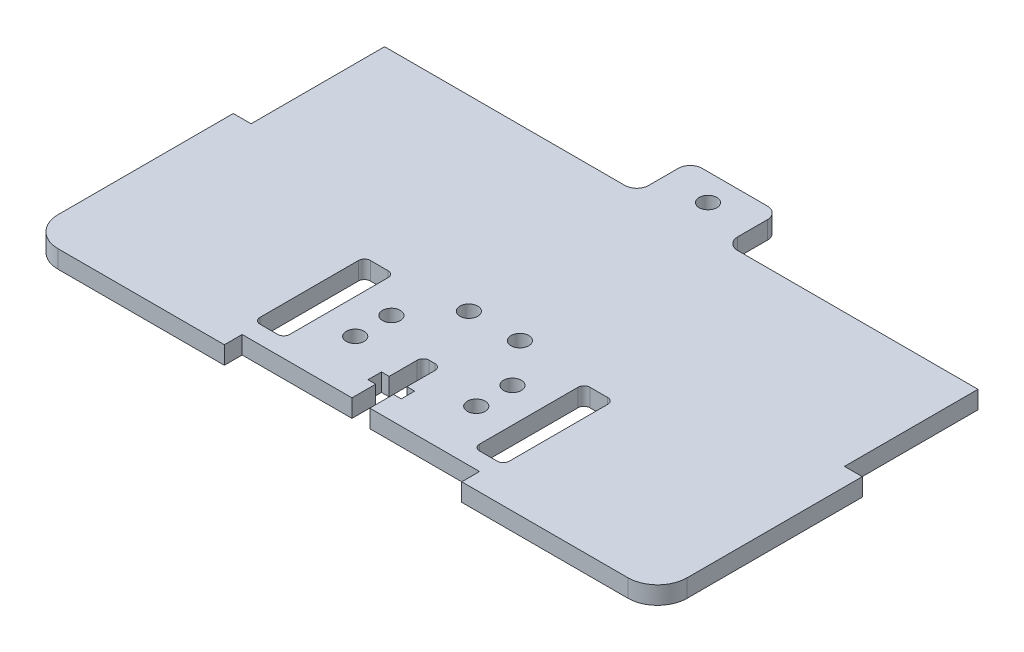
SolidWorks part; units mm, degrees
material "Acrylic (Medium-high impact)"
ref_plane "Plano frontal" through (0, 0, 0) normal (0, 0, 1) x (1, 0, 0)
ref_plane "Plano superior" through (0, 0, 0) normal (0, 1, 0) x (1, 0, 0)
ref_plane "Plano direito" through (0, 0, 0) normal (1, 0, 0) x (0, 0, -1)
sketch "Sketch1" plane through (0, 0, 0) normal (0, 1, 0) x (1, 0, 0)
  line L1 (-53, 28.5) -> (53, 28.5)
  line L2 (-53, 28.5) -> (-53, -28.5)
  line L3 (-53, -28.5) -> (53, -28.5)
  line L4 (53, 28.5) -> (53, -28.5)
  point P4 (0, 28.5)
  point P6 (-53, 0)
  dimension "D1" = 57
  dimension "D2" = 106
extrude "Boss-Extrude1" add sketch "Sketch1" along normal mid plane 3
sketch "Sketch2" plane through (0, 0, 0) normal (0, 1, 0) x (1, 0, 0)
  line L0 (0, -1.65) -> (0, 1.65) construction
  line L1 (-53, 28.5) -> (-50, 28.5)
  line L2 (-53, 28.5) -> (-53, 6)
  line L3 (-53, 6) -> (-50, 6)
  line L4 (-50, 28.5) -> (-50, 6)
  line L5 (50, 28.5) -> (50, 6)
  line L6 (53, 6) -> (50, 6)
  line L7 (53, 28.5) -> (53, 6)
  line L8 (53, 28.5) -> (50, 28.5)
  line L9 (-53, -28.5) -> (53, -28.5) construction
  line L10 (-20, -28.5) -> (20, -28.5)
  line L11 (-20, -28.5) -> (-20, -25.5)
  line L12 (-20, -25.5) -> (20, -25.5)
  line L13 (20, -28.5) -> (20, -25.5)
  point P17 (0, -25.5)
  dimension "D1" = 3
  dimension "D2" = 22.5
  dimension "D3" = 3
  dimension "D4" = 40
extrude "Cut-Extrude1" cut sketch "Sketch2" against normal through all both and the other way through all
sketch "Sketch4" plane through (0, 0, 0) normal (0, 1, 0) x (1, 0, 0)
  line L0 (50, 28.5) -> (-50, 28.5) construction
  line L1 (-7.5, 28.5) -> (7.5, 28.5)
  line L2 (-7.5, 28.5) -> (-7.5, 37.5)
  line L3 (-7.5, 37.5) -> (7.5, 37.5)
  line L4 (7.5, 28.5) -> (7.5, 37.5)
  point P6 (0, 28.5)
  dimension "D1" = 15
  dimension "D2" = 9
extrude "Boss-Extrude2" add sketch "Sketch4" along normal mid plane 3
fillet "Fillet1" radius 2 4 edges at (7.5, 0, -37.5) (-7.5, 0, -37.5) (7.5, 0, -28.5) (-7.5, 0, -28.5)
sketch "Sketch3" plane through (0, 0, 0) normal (0, 1, 0) x (1, 0, 0)
  line L0 (20, -25.5) -> (-20, -25.5) construction
  line L1 (-1.5, -25.5) -> (1.5, -25.5)
  line L2 (-1.5, -25.5) -> (-1.5, -21.5)
  line L3 (-0.5, -13.5) -> (0.5, -13.5)
  line L4 (1.5, -25.5) -> (1.5, -21.5)
  line L5 (1.5, -19.23) -> (2.8, -19.23)
  line L6 (-2.8, -19.23) -> (-1.5, -19.23)
  line L7 (-2.8, -19.23) -> (-2.8, -21.5)
  line L8 (-2.8, -21.5) -> (-1.5, -21.5)
  line L9 (2.8, -19.23) -> (2.8, -21.5)
  line L10 (-1.5, -19.23) -> (-1.5, -14.5)
  line L11 (1.5, -21.5) -> (2.8, -21.5)
  line L12 (1.5, -19.23) -> (1.5, -14.5)
  arc A0 (0.5, -13.5) -> (1.5, -14.5) centre (0.5, -14.5) cw
  arc A1 (-1.5, -14.5) -> (-0.5, -13.5) centre (-0.5, -14.5) cw
  point P6 (0, -13.5)
  dimension "D7" = 1
  dimension "D1" = 3
  dimension "D2" = 2.27
  dimension "D3" = 1.3
  dimension "D4" = 1.3
  dimension "D5" = 4
  dimension "D6" = 12
extrude "Cut-Extrude2" cut sketch "Sketch3" against normal through all both and the other way through all
sketch "Sketch5" plane through (0, 0, 0) normal (0, 1, 0) x (1, 0, 0)
  line L0 (-9.5, 28.5) -> (-50, 28.5) construction
  circle A0 centre (0, 33) radius 1.5
  dimension "D1" = 3
  dimension "D2" = 4.5
extrude "Cut-Extrude3" cut sketch "Sketch5" against normal through all both and the other way through all
fillet "Fillet2" radius 5 2 edges at (53, 0, 28.5) (-53, 0, 28.5)
sketch "Sketch6" plane through (0, 0, 0) normal (0, 1, 0) x (1, 0, 0)
  line L0 (0.5, -13.5) -> (-0.5, -13.5) construction
  line L3 (0, -1.65) -> (0, 1.65) construction
  line L4 (-50, 6) -> (-50, -28.0826) construction
  line L7 (-4.3, -3) -> (4.3, -3) construction
  circle A0 centre (-4.3, -3) radius 1.5
  circle A1 centre (4.3, -3) radius 1.5
  arc A4 (-53, -23.5) -> (-48, -28.5) centre (-48, -23.5) ccw construction
  circle A5 centre (10.2, -10.15) radius 1.5
  circle A11 centre (10.2, -16.25) radius 1.5
  circle A12 centre (-10.2, -16.25) radius 1.5
  circle A13 centre (-10.2, -10.15) radius 1.5
  point P4 (0, -3)
  dimension "D1" = 3
  dimension "D2" = 8.6
  dimension "D3" = 10.5
  dimension "D4" = 3
extrude "Cut-Extrude4" cut sketch "Sketch6" against normal through all both and the other way through all
sketch "Esboço1" plane through (0, 1.5, 0) normal (0, 1, 0) x (1, 0, 0)
  line L0 (-1.5, -25.5) -> (-20, -25.5) construction
  line L1 (-22, -2.9) -> (-15, -2.9) construction
  line L2 (-22, -2.9) -> (-22, -23.5) construction
  line L3 (-22, -23.5) -> (-15, -23.5) construction
  line L4 (-15, -2.9) -> (-15, -23.5) construction
  line L5 (-20, -3.9) -> (-17, -3.9)
  line L6 (-16, -4.9) -> (-16, -21.5)
  line L7 (-20, -22.5) -> (-17, -22.5)
  line L8 (-21, -4.9) -> (-21, -21.5)
  line L18 (-16, -3.9) -> (-16, -22.5) construction
  line L19 (-21, -22.5) -> (-16, -22.5) construction
  line L20 (-21, -3.9) -> (-21, -22.5) construction
  line L21 (-21, -3.9) -> (-16, -3.9) construction
  line L22 (0, -1.65) -> (0, 1.65) construction
  line L23 (15, -2.9) -> (15, -23.5) construction
  line L24 (22, -23.5) -> (15, -23.5) construction
  line L25 (22, -2.9) -> (22, -23.5) construction
  line L26 (22, -2.9) -> (15, -2.9) construction
  line L27 (21, -4.9) -> (21, -21.5)
  line L28 (20, -22.5) -> (17, -22.5)
  line L29 (16, -4.9) -> (16, -21.5)
  line L30 (20, -3.9) -> (17, -3.9)
  arc A0 (-16, -21.5) -> (-17, -22.5) centre (-17, -21.5) cw
  arc A1 (-20, -22.5) -> (-21, -21.5) centre (-20, -21.5) cw
  arc A2 (-20, -3.9) -> (-21, -4.9) centre (-20, -4.9) ccw
  arc A3 (-17, -3.9) -> (-16, -4.9) centre (-17, -4.9) cw
  arc A4 (17, -3.9) -> (16, -4.9) centre (17, -4.9) ccw
  arc A5 (20, -3.9) -> (21, -4.9) centre (20, -4.9) cw
  arc A6 (20, -22.5) -> (21, -21.5) centre (20, -21.5) ccw
  arc A7 (16, -21.5) -> (17, -22.5) centre (17, -21.5) ccw
  dimension "D3" = 1
  dimension "D1" = 2
  dimension "D2" = 1
extrude "Corte-extrusão1" cut sketch "Esboço1" against normal through all both and the other way through all
